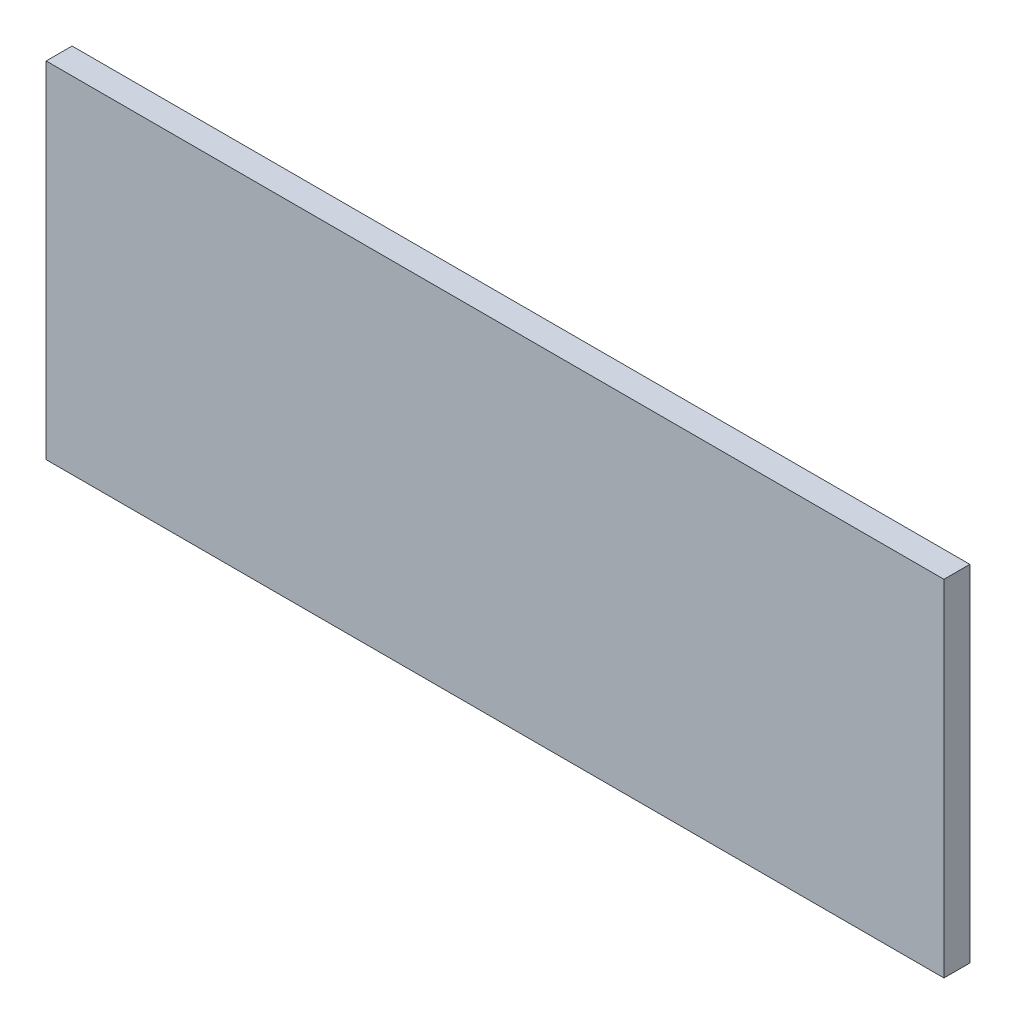
SolidWorks part; units mm, degrees
ref_plane "Front Plane" through (0, 0, 0) normal (0, 0, 1) x (1, 0, 0)
ref_plane "Top Plane" through (0, 0, 0) normal (0, 1, 0) x (1, 0, 0)
ref_plane "Right Plane" through (0, 0, 0) normal (1, 0, 0) x (0, 0, -1)
sketch "Sketch1" plane through (0, 0, 0) normal (0, 0, 1) x (1, 0, 0)
  line L1 (-55.88, 21.23) -> (48.12, 21.23)
  line L2 (-55.88, 21.23) -> (-55.88, -18.77)
  line L3 (-55.88, -18.77) -> (48.12, -18.77)
  line L4 (48.12, 21.23) -> (48.12, -18.77)
  dimension "D1" = 104
  dimension "D2" = 40
extrude "Boss-Extrude1" add sketch "Sketch1" along normal blind 3
